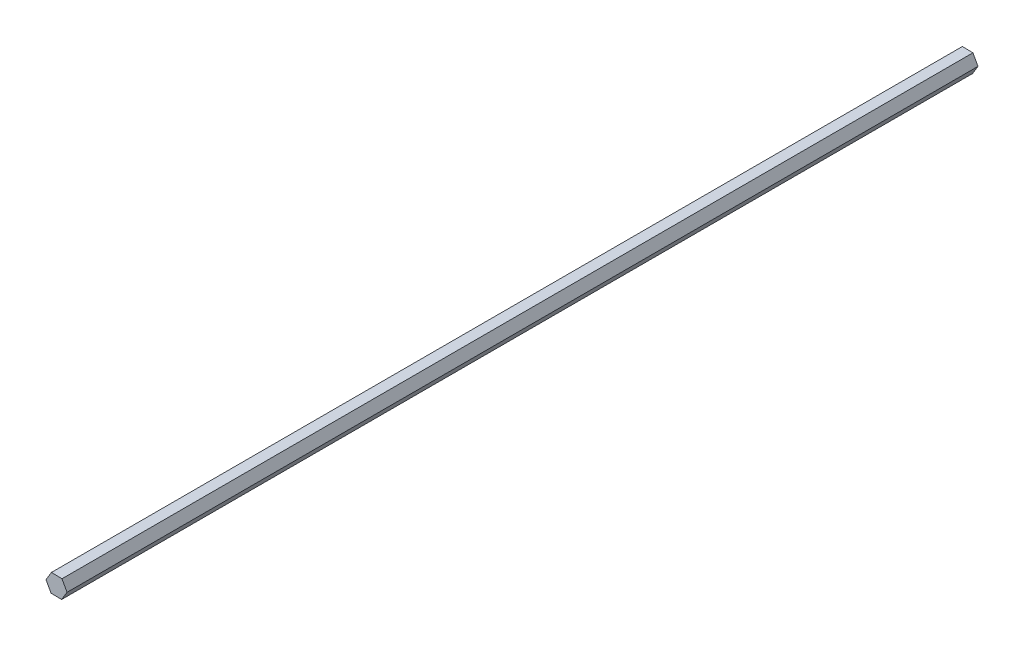
SolidWorks part; units mm, degrees
ref_plane "Front Plane" through (0, 0, 0) normal (0, 0, 1) x (1, 0, 0)
ref_plane "Top Plane" through (0, 0, 0) normal (0, 1, 0) x (1, 0, 0)
ref_plane "Right Plane" through (0, 0, 0) normal (1, 0, 0) x (0, 0, -1)
sketch "Sketch1" plane through (0, 0, 0) normal (0, 0, 1) x (1, 0, 0)
  line L1 (3.5226, -6.4308) -> (7.3305, -0.1647)
  line L2 (7.3305, -0.1647) -> (3.8079, 6.266)
  line L3 (3.8079, 6.266) -> (-3.5226, 6.4308)
  line L4 (-3.5226, 6.4308) -> (-7.3305, 0.1647)
  line L5 (-7.3305, 0.1647) -> (-3.8079, -6.266)
  line L6 (-3.8079, -6.266) -> (3.5226, -6.4308)
  circle A0 centre (0, 0) radius 6.35 construction
  dimension "D1" = 12.7
extrude "Boss-Extrude1" add sketch "Sketch1" along normal blind 635
